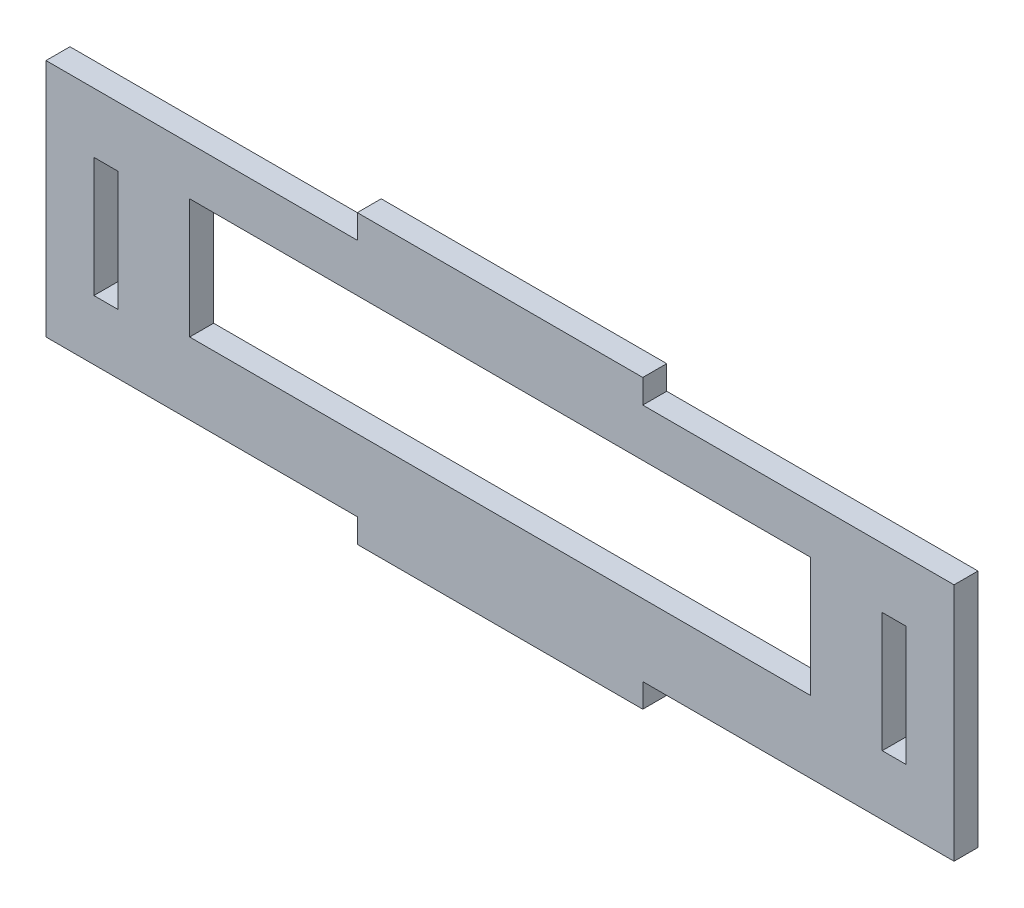
SolidWorks part; units mm, degrees
ref_plane "Front Plane" through (0, 0, 0) normal (0, 0, 1) x (1, 0, 0)
ref_plane "Top Plane" through (0, 0, 0) normal (0, 1, 0) x (1, 0, 0)
ref_plane "Right Plane" through (0, 0, 0) normal (1, 0, 0) x (0, 0, -1)
sketch "Sketch1" plane through (0, 0, 0) normal (0, 0, 1) x (1, 0, 0)
  line L0 (0, 0) -> (24, 0)
  line L2 (0, 0) -> (0, 20) construction
  line L4 (71.848, 0) -> (71.848, 20) construction
  line L5 (24, 0) -> (24, -2)
  line L6 (24, -2) -> (47.848, -2)
  line L7 (47.848, -2) -> (47.848, 0)
  line L8 (47.848, 0) -> (71.848, 0)
  line L9 (0, 20) -> (24, 20)
  line L10 (24, 20) -> (24, 22)
  line L11 (24, 22) -> (47.848, 22)
  line L12 (47.848, 22) -> (47.848, 20)
  line L13 (47.848, 20) -> (71.848, 20)
  line L14 (71.848, 20) -> (73.848, 20)
  line L15 (10, 6) -> (61.848, 6)
  line L16 (10, 6) -> (10, 16)
  line L17 (10, 16) -> (61.848, 16)
  line L18 (61.848, 6) -> (61.848, 16)
  line L19 (2, 15) -> (4, 15)
  line L20 (2, 15) -> (2, 5)
  line L21 (2, 5) -> (4, 5)
  line L22 (4, 15) -> (4, 5)
  line L23 (67.848, 15) -> (69.848, 15)
  line L24 (67.848, 15) -> (67.848, 5)
  line L25 (67.848, 5) -> (69.848, 5)
  line L26 (69.848, 15) -> (69.848, 5)
  line L27 (73.848, 20) -> (73.848, 0)
  line L28 (73.848, 0) -> (71.848, 0)
  line L29 (0, 20) -> (-2, 20)
  line L30 (-2, 20) -> (-2, 0)
  line L31 (-2, 0) -> (0, 0)
  dimension "D1" = 20
  dimension "D2" = 6
  dimension "D3" = 10
  dimension "D4" = 10
  dimension "D5" = 10
  dimension "D6" = 2
  dimension "D7" = 5
  dimension "D8" = 5
  dimension "D9" = 2
extrude "Boss-Extrude1" add sketch "Sketch1" along normal blind 2
